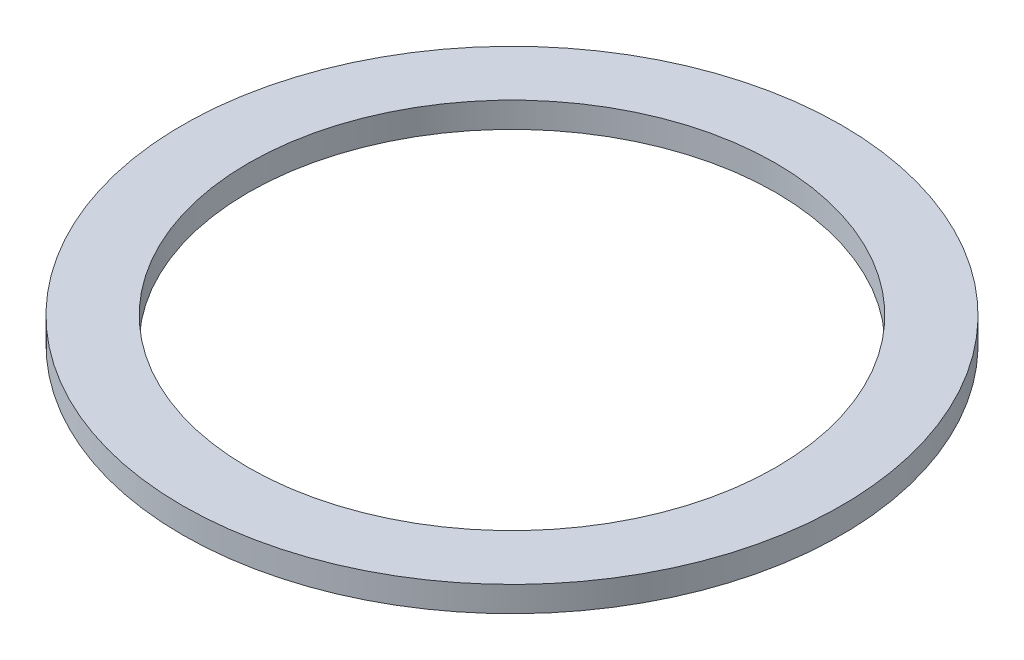
SolidWorks part; units mm, degrees
ref_plane "Front Plane" through (0, 0, 0) normal (0, 0, 1) x (1, 0, 0)
ref_plane "Top Plane" through (0, 0, 0) normal (0, 1, 0) x (1, 0, 0)
ref_plane "Right Plane" through (0, 0, 0) normal (1, 0, 0) x (0, 0, -1)
sketch "Sketch2" plane through (0, 0, 0) normal (0, 1, 0) x (1, 0, 0)
  circle A0 centre (0, 0) radius 39.624
  circle A1 centre (0, 0) radius 49.53
  dimension "D1" = 99.06
  dimension "D2" = 79.248
extrude "Boss-Extrude1" add sketch "Sketch2" along normal blind 3.81 contours A1 A0
